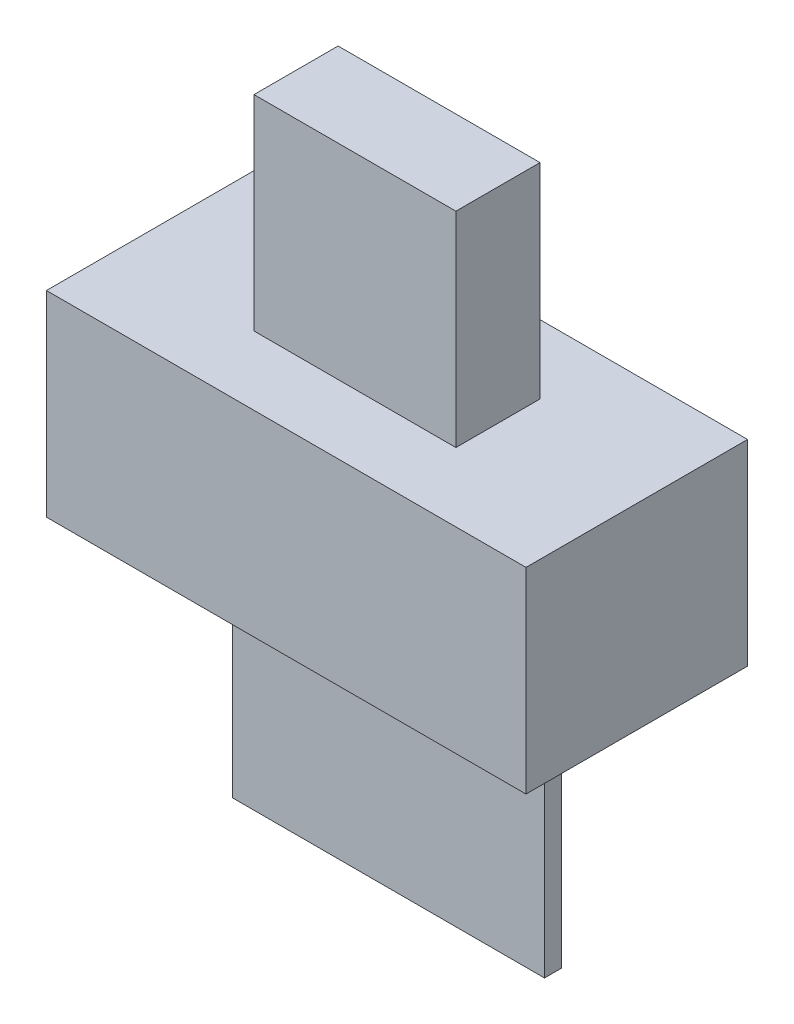
SolidWorks part; units mm, degrees
ref_plane "Front" through (0, 0, 0) normal (0, 0, 1) x (1, 0, 0)
ref_plane "Top" through (0, 0, 0) normal (0, 1, 0) x (1, 0, 0)
ref_plane "Right" through (0, 0, 0) normal (1, 0, 0) x (0, 0, -1)
sketch "草图1" plane through (0, 0, 0) normal (0, 0, 1) x (1, 0, 0)
  line L1 (0, 0) -> (8.55, 0)
  line L2 (0, 0) -> (0, 3.5)
  line L3 (0, 3.5) -> (8.55, 3.5)
  line L4 (8.55, 0) -> (8.55, 3.5)
  dimension "D1" = 8.55
  dimension "D2" = 3.5
extrude "凸台-拉伸1" add sketch "草图1" along normal blind 3.95
sketch "草图2" plane through (0, 3.5, 0) normal (0, 1, 0) x (1, 0, 0)
  line L0 (8.55, 0) -> (0, 0) construction
  line L1 (2.475, -1.225) -> (6.075, -1.225)
  line L2 (2.475, -1.225) -> (2.475, -2.725)
  line L3 (2.475, -2.725) -> (6.075, -2.725)
  line L4 (6.075, -1.225) -> (6.075, -2.725)
  line L5 (2.475, -1.225) -> (6.075, -2.725) construction
  line L6 (2.475, -2.725) -> (6.075, -1.225) construction
  line L7 (0, -3.95) -> (0, 0) construction
  point P0 (4.275, -1.975)
  point P8 (4.275, 0)
  point P11 (0, -1.975)
  dimension "D1" = 1.5
  dimension "D2" = 3.6
extrude "凸台-拉伸2" add sketch "草图2" along normal blind 3.65
sketch "草图3" plane through (0, 0, 0) normal (0, -1, 0) x (1, 0, 0)
  line L0 (0, 3.95) -> (8.55, 3.95) construction
  line L1 (1.495, 2.125) -> (7.055, 2.125)
  line L2 (1.495, 2.125) -> (1.495, 1.825)
  line L3 (1.495, 1.825) -> (7.055, 1.825)
  line L4 (7.055, 2.125) -> (7.055, 1.825)
  line L5 (1.495, 2.125) -> (7.055, 1.825) construction
  line L6 (1.495, 1.825) -> (7.055, 2.125) construction
  line L7 (0, 3.95) -> (0, 0) construction
  point P0 (4.275, 1.975)
  point P7 (4.275, 3.95)
  point P10 (0, 1.975)
  dimension "D1" = 0.3
extrude "凸台-拉伸3" add sketch "草图3" along normal blind 4.5 contours L1 L4 L3 L2
